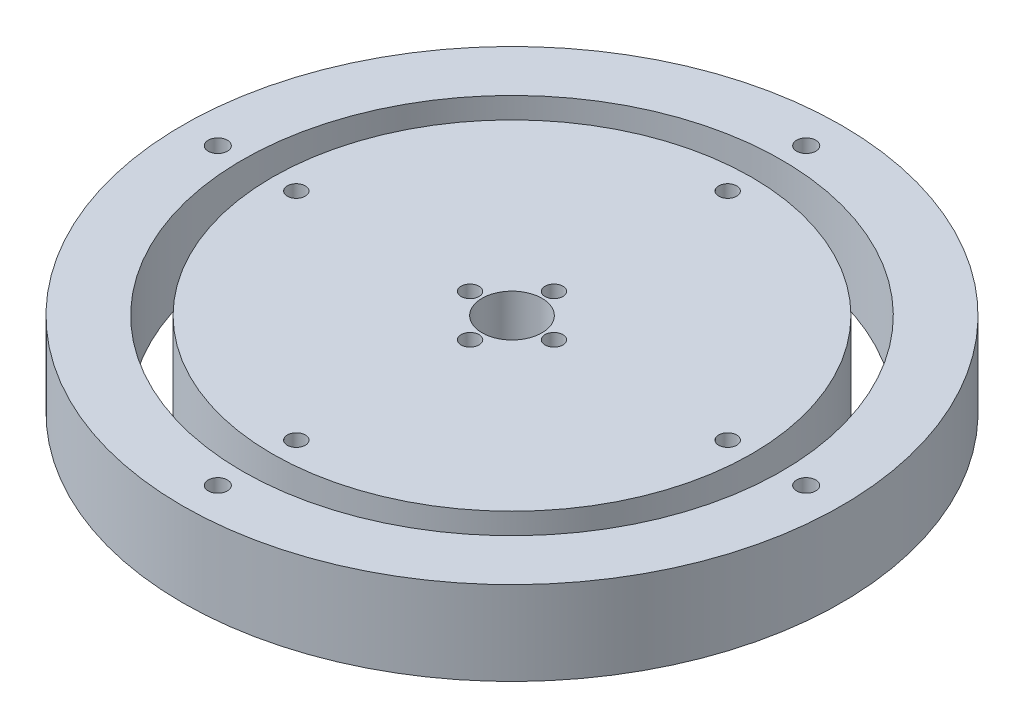
SolidWorks part; units mm, degrees
ref_plane "前视基准面" through (0, 0, 0) normal (0, 0, 1) x (1, 0, 0)
ref_plane "上视基准面" through (0, 0, 0) normal (0, 1, 0) x (1, 0, 0)
ref_plane "右视基准面" through (0, 0, 0) normal (1, 0, 0) x (0, 0, -1)
other "Configuration Table"
sketch "草图1" plane through (0, 0, 0) normal (0, 1, 0) x (1, 0, 0)
  circle A0 centre (0, 0) radius 40
  circle A1 centre (0, 0) radius 5
  circle A3 centre (7, 0) radius 1.5
  circle A4 centre (0, 7) radius 1.5
  circle A5 centre (-7, 0) radius 1.5
  circle A6 centre (0, -7) radius 1.5
  circle A8 centre (-36, 0) radius 1.5
  circle A9 centre (36, 0) radius 1.5
  circle A10 centre (0, 36) radius 1.5
  circle A11 centre (0, -36) radius 1.5
  circle A12 centre (0, 0) radius 45
  circle A13 centre (0, 0) radius 55
  circle A15 centre (-49.1, 0) radius 1.6
  circle A16 centre (49.1, 0) radius 1.6
  circle A17 centre (0, 49.1) radius 1.6
  circle A18 centre (0, -49.1) radius 1.6
  point P22 (0, 0)
  point P31 (0, 0)
  point P32 (0, 0)
  point P33 (0, 0)
extrude "凸台-拉伸9" add sketch "草图1" along normal blind 14 contours A13 A18 A17 A16 A15 A12 | A0 A11 A10 A9 A8 A6 A5 A4 A3 A1
